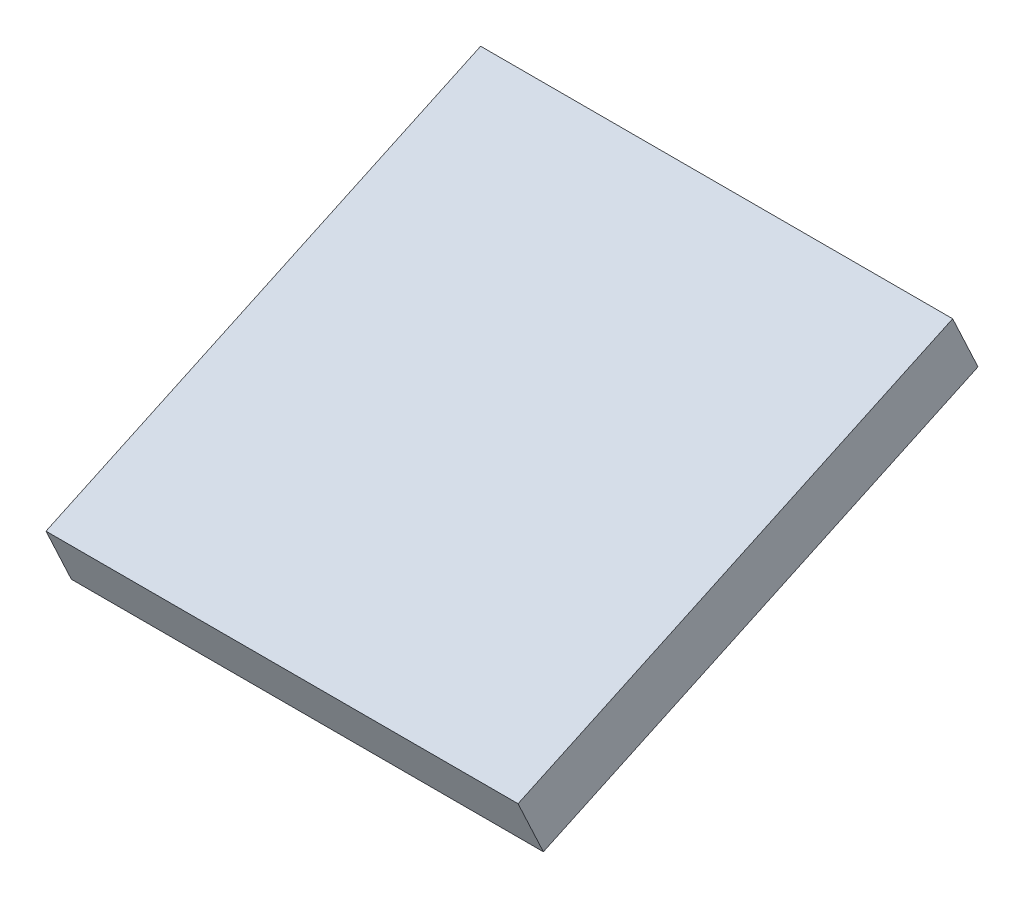
SolidWorks part; units mm, degrees
ref_plane "Front Plane" through (0, 0, 0) normal (0, 0, 1) x (1, 0, 0)
ref_plane "Top Plane" through (0, 0, 0) normal (0, 1, 0) x (1, 0, 0)
ref_plane "Right Plane" through (0, 0, 0) normal (1, 0, 0) x (0, 0, -1)
sketch "Sketch3" plane through (0, 0, 0) normal (1, 0, 0) x (0, 0, -1)
  line L0 (0, 0) -> (0, 42.938) construction
  line L1 (-92.0809, 0) -> (0, 42.938)
  line L2 (0, 42.938) -> (-5.3673, 54.4481)
  line L3 (-5.3673, 54.4481) -> (-97.4481, 11.5101)
  line L4 (-97.4481, 11.5101) -> (-92.0809, 0)
  line L5 (-92.0809, 0) -> (0, 0) construction
  dimension "D1" = 101.6
  dimension "D2" = 12.7
  dimension "D3" = 25
extrude "Boss-Extrude1" add sketch "Sketch3" against normal blind 100.0125
